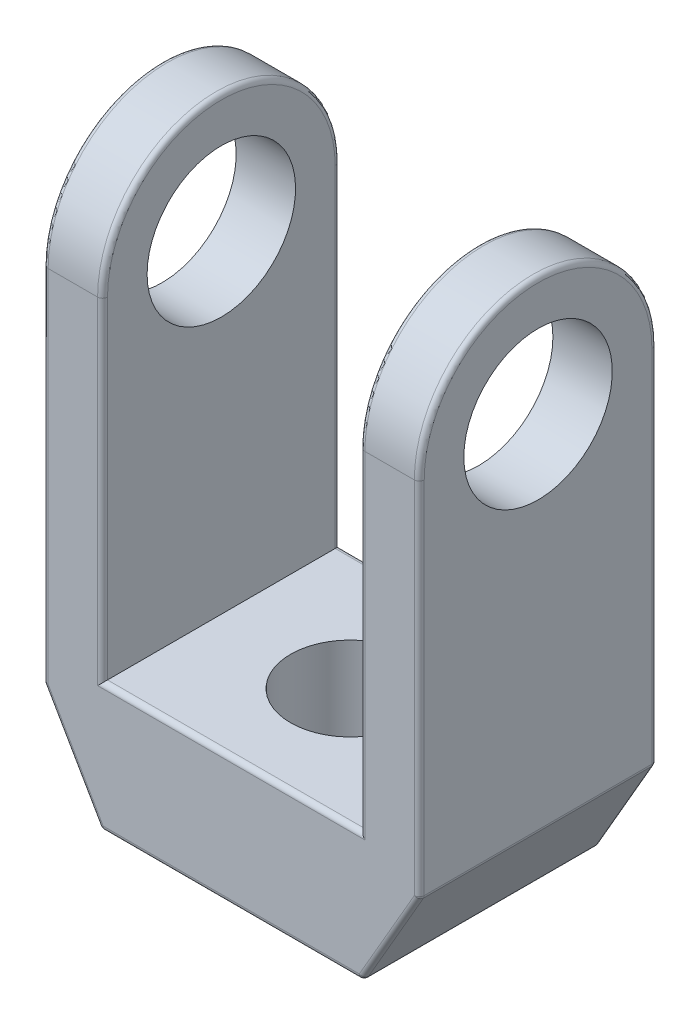
SolidWorks part; units mm, degrees
ref_plane "Front Plane" through (0, 0, 0) normal (0, 0, 1) x (1, 0, 0)
ref_plane "Top Plane" through (0, 0, 0) normal (0, 1, 0) x (1, 0, 0)
ref_plane "Right Plane" through (0, 0, 0) normal (1, 0, 0) x (0, 0, -1)
sketch "Sketch1" plane through (0, 0, 0) normal (0, 0, 1) x (1, 0, 0)
  line L0 (-38, -49.5) -> (-26.453, -69.5)
  line L2 (-38, -49.5) -> (-38, 49.5)
  line L3 (-38, 49.5) -> (38, 49.5)
  line L4 (38, -49.5) -> (38, 49.5)
  line L5 (-38, -49.5) -> (38, 49.5) construction
  line L6 (-38, 49.5) -> (38, -49.5) construction
  line L7 (-26.453, -69.5) -> (26.453, -69.5)
  line L8 (26.453, -69.5) -> (38, -49.5)
  point P0 (0, 0)
  point P6 (0, -69.5)
  dimension "D1" = 60
  dimension "D2" = 60
  dimension "D3" = 119
  dimension "D4" = 76
  dimension "D5" = 20
extrude "Boss-Extrude1" add sketch "Sketch1" along normal mid plane 48
sketch "Sketch2" plane through (0, 0, 24) normal (0, 0, 1) x (1, 0, 0)
  line L0 (-26, 49.5) -> (-26, -43.5)
  line L1 (38, 49.5) -> (-38, 49.5) construction
  line L2 (-26, -43.5) -> (26, -43.5)
  line L3 (26, -43.5) -> (26, 49.5)
  line L4 (-38, 49.5) -> (-38, -49.5) construction
  line L5 (38, -49.5) -> (38, 49.5) construction
  line L6 (-26.453, -69.5) -> (26.453, -69.5) construction
  line L7 (-26, 49.5) -> (26, 49.5)
  dimension "D1" = 12
  dimension "D2" = 12
  dimension "D3" = 26
extrude "Cut-Extrude1" cut sketch "Sketch2" against normal blind 48
sketch "Sketch3" plane through (-38, 0, 0) normal (-1, 0, 0) x (0, 0, 1)
  line L0 (24, 49.5) -> (-24, 49.5) construction
  line L1 (-24, 23.5) -> (-24, 49.5)
  line L2 (-24, 23.5) -> (24, 23.5) construction
  line L3 (-24, 49.5) -> (24, 49.5)
  line L4 (24, 49.5) -> (24, 23.5)
  arc A0 (-24, 23.5) -> (24, 23.5) centre (0, 23.5) cw
  dimension "D1" = 24
  dimension "D2" = 26
extrude "Cut-Extrude2" cut sketch "Sketch3" against normal blind 105
sketch "Sketch4" plane through (-38, 0, 0) normal (-1, 0, 0) x (0, 0, 1)
  circle A0 centre (0, 23.5) radius 15
  arc A1 (24, 23.5) -> (-24, 23.5) centre (0, 23.5) ccw construction
  dimension "D1" = 30
extrude "Cut-Extrude3" cut sketch "Sketch4" against normal blind 105
sketch "Sketch5" plane through (0, -43.5, 0) normal (0, 1, 0) x (1, 0, 0)
  line L0 (-26, -24) -> (26, 24) construction
  circle A0 centre (0, 0) radius 12
  point P3 (0, 0)
  dimension "D1" = 24
extrude "Cut-Extrude4" cut sketch "Sketch5" against normal blind 105
fillet "Fillet1" radius 1 25 edges at (-26, 47.5, 0) (26, 47.5, 0) (38, 47.5, 0) (-38, 47.5, 0) (38, -13, -24) (26, -10, -24) (0, -43.5, -24) (-26, -10, -24) (-38, -13, -24) (-38, -49.5, 0) (-32.2265, -59.5, -24) (-26, -10, 24) (0, -43.5, 24) (26, -10, 24) (38, -13, 24) (-32.2265, -59.5, 24) (-38, -13, 24) (-26.453, -69.5, 0) (0, -69.5, 24) (0, -69.5, -24) (0, -69.5, 12) (26.453, -69.5, 0) (32.2265, -59.5, 24) (38, -49.5, 0) (32.2265, -59.5, -24)
